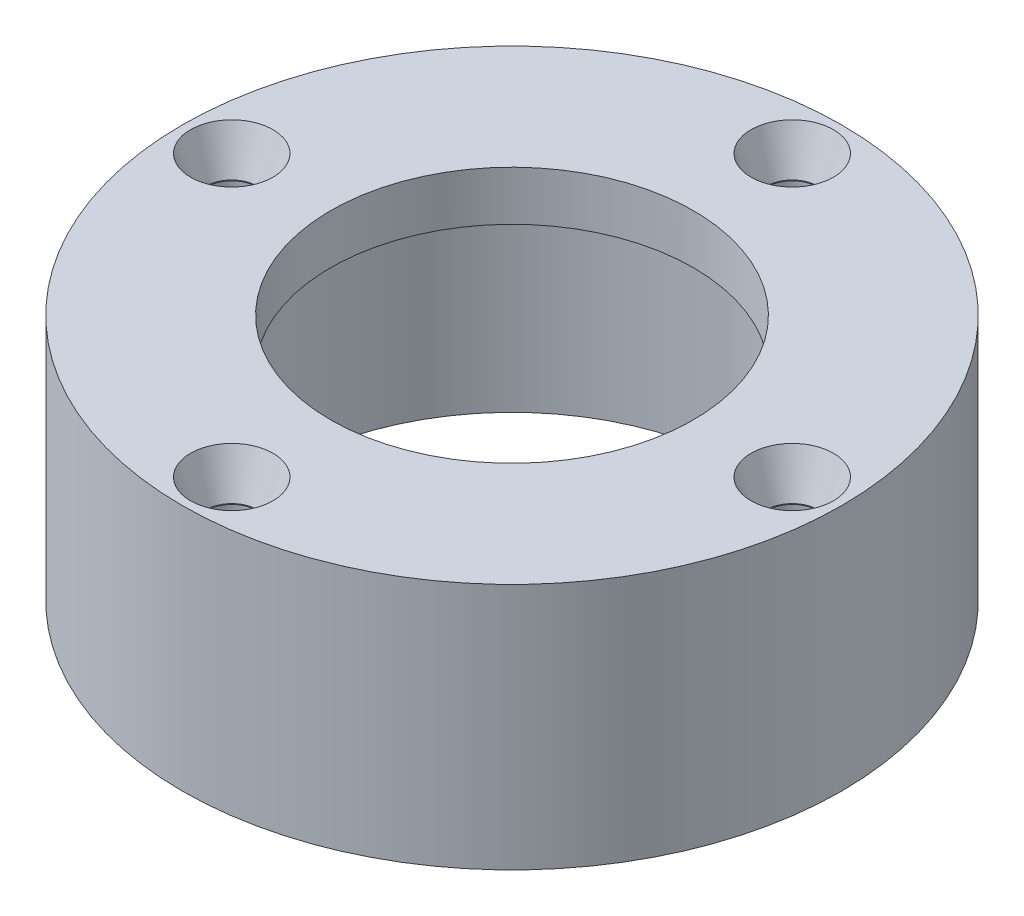
SolidWorks part; units mm, degrees
ref_plane "Front Plane" through (0, 0, 0) normal (0, 0, 1) x (1, 0, 0)
ref_plane "Top Plane" through (0, 0, 0) normal (0, 1, 0) x (1, 0, 0)
ref_plane "Right Plane" through (0, 0, 0) normal (1, 0, 0) x (0, 0, -1)
sketch "Sketch1" plane through (0, 0, 0) normal (0, 1, 0) x (1, 0, 0)
  circle A0 centre (0, 0) radius 20
extrude "Boss-Extrude1" add sketch "Sketch1" along normal blind 15
sketch "Sketch2" plane through (0, 0, 0) normal (0, -1, 0) x (-1, 0, 0)
  circle A1 centre (0, -17) radius 1.5
  circle A2 centre (-17, 0) radius 1.5
  circle A3 centre (0, 17) radius 1.5
  circle A4 centre (17, 0) radius 1.5
  point P14 (0, 0)
  dimension "D1" = 17
  dimension "D2" = 4
extrude "Cut-Extrude1" cut sketch "Sketch2" against normal blind 20
sketch "Sketch3" plane through (0, 15, 0) normal (0, 1, 0) x (1, 0, 0)
  circle A0 centre (0, 17) radius 2.5
  circle A1 centre (17, 0) radius 2.5
  circle A2 centre (0, -17) radius 2.5
  circle A3 centre (-17, 0) radius 2.5
  point P12 (0, 0)
  dimension "D1" = 4
extrude "Cut-Extrude2" cut sketch "Sketch3" against normal blind 2.5 draft 20.5
sketch "Sketch4" plane through (0, 0, 0) normal (0, -1, 0) x (1, 0, 0)
  circle A0 centre (0, 0) radius 14
extrude "Cut-Extrude3" cut sketch "Sketch4" against normal blind 12
sketch "Sketch5" plane through (0, 15, 0) normal (0, 1, 0) x (1, 0, 0)
  circle A0 centre (0, 0) radius 11
extrude "Cut-Extrude4" cut sketch "Sketch5" against normal blind 12
